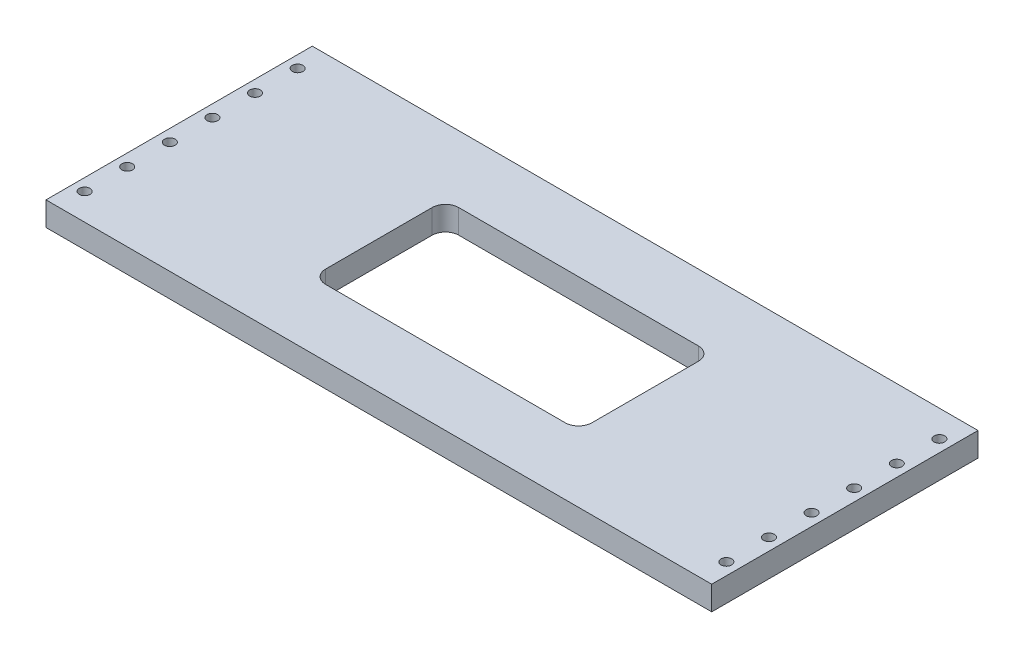
SolidWorks part; units mm, degrees
ref_plane "Front Plane" through (0, 0, 0) normal (0, 0, 1) x (1, 0, 0)
ref_plane "Top Plane" through (0, 0, 0) normal (0, 1, 0) x (1, 0, 0)
ref_plane "Right Plane" through (0, 0, 0) normal (1, 0, 0) x (0, 0, -1)
sketch "Sketch1" plane through (0, 0, 0) normal (0, 1, 0) x (1, 0, 0)
  line L1 (0, 0) -> (500, 0)
  line L2 (0, 0) -> (0, 200)
  line L3 (0, 200) -> (500, 200)
  line L4 (500, 0) -> (500, 200)
  dimension "D1" = 500
  dimension "D2" = 200
extrude "Boss-Extrude1" add sketch "Sketch1" along normal blind 18
sketch "Sketch2" plane through (0, 18, 0) normal (0, 1, 0) x (1, 0, 0)
  line L0 (9, 0) -> (9, 200) construction
  line L1 (0, 0) -> (500, 0) construction
  line L2 (500, 200) -> (0, 200) construction
  line L3 (0, 200) -> (0, 0) construction
  line L4 (250, 200) -> (250, 0) construction
  line L5 (491, 0) -> (491, 200) construction
  circle A0 centre (9, 180) radius 4
  circle A1 centre (9, 148) radius 4
  circle A2 centre (9, 116) radius 4
  circle A3 centre (9, 84) radius 4
  circle A4 centre (9, 52) radius 4
  circle A5 centre (9, 20) radius 4
  circle A6 centre (491, 20) radius 4
  circle A7 centre (491, 52) radius 4
  circle A8 centre (491, 84) radius 4
  circle A9 centre (491, 116) radius 4
  circle A10 centre (491, 148) radius 4
  circle A11 centre (491, 180) radius 4
  dimension "D2" = 8
  dimension "D3" = 20
  dimension "D1" = 9
  dimension "D4" = 6
extrude "Cut-Extrude1" cut sketch "Sketch2" against normal blind 10
sketch "Sketch3" plane through (0, 18, 0) normal (0, 1, 0) x (1, 0, 0)
  line L0 (500, 200) -> (0, 200) construction
  line L1 (160, 150) -> (340, 150)
  line L2 (150, 140) -> (150, 60)
  line L3 (160, 50) -> (340, 50)
  line L4 (350, 140) -> (350, 60)
  line L5 (0, 0) -> (500, 0) construction
  line L6 (0, 200) -> (0, 0) construction
  line L7 (500, 0) -> (500, 200) construction
  arc A0 (340, 150) -> (350, 140) centre (340, 140) cw
  arc A1 (340, 50) -> (350, 60) centre (340, 60) ccw
  arc A2 (150, 60) -> (160, 50) centre (160, 60) ccw
  arc A3 (160, 150) -> (150, 140) centre (160, 140) ccw
  dimension "D5" = 10
  dimension "D1" = 50
  dimension "D2" = 50
  dimension "D3" = 150
  dimension "D4" = 150
extrude "Cut-Extrude2" cut sketch "Sketch3" against normal blind 30
